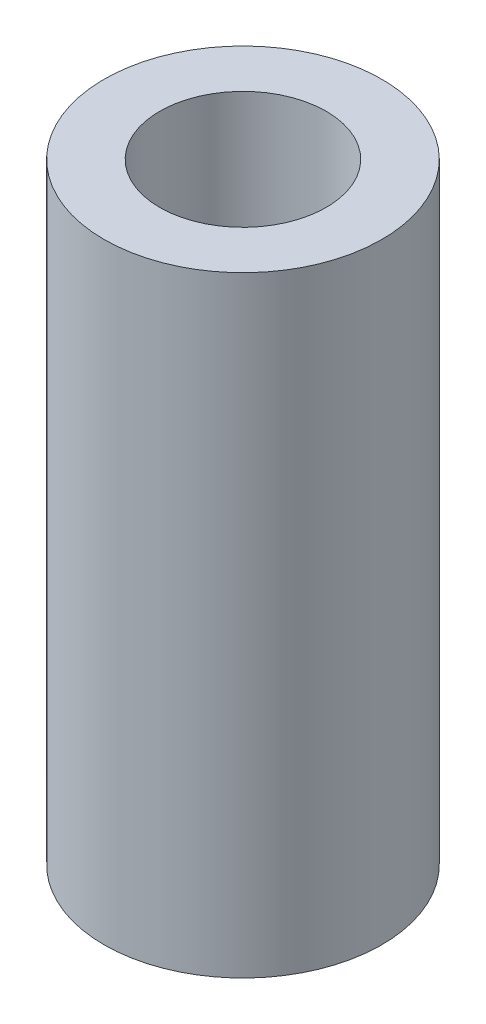
SolidWorks part; units mm, degrees
ref_plane "Front Plane" through (0, 0, 0) normal (0, 0, 1) x (1, 0, 0)
ref_plane "Top Plane" through (0, 0, 0) normal (0, 1, 0) x (1, 0, 0)
ref_plane "Right Plane" through (0, 0, 0) normal (1, 0, 0) x (0, 0, -1)
sketch "Sketch1" plane through (0, 0, 0) normal (0, 1, 0) x (1, 0, 0)
  circle A0 centre (0, 0) radius 2.5
  circle A1 centre (0, 0) radius 1.5
  dimension "D1" = 3
  dimension "D2" = 1
extrude "Boss-Extrude1" add sketch "Sketch1" along normal blind 11
